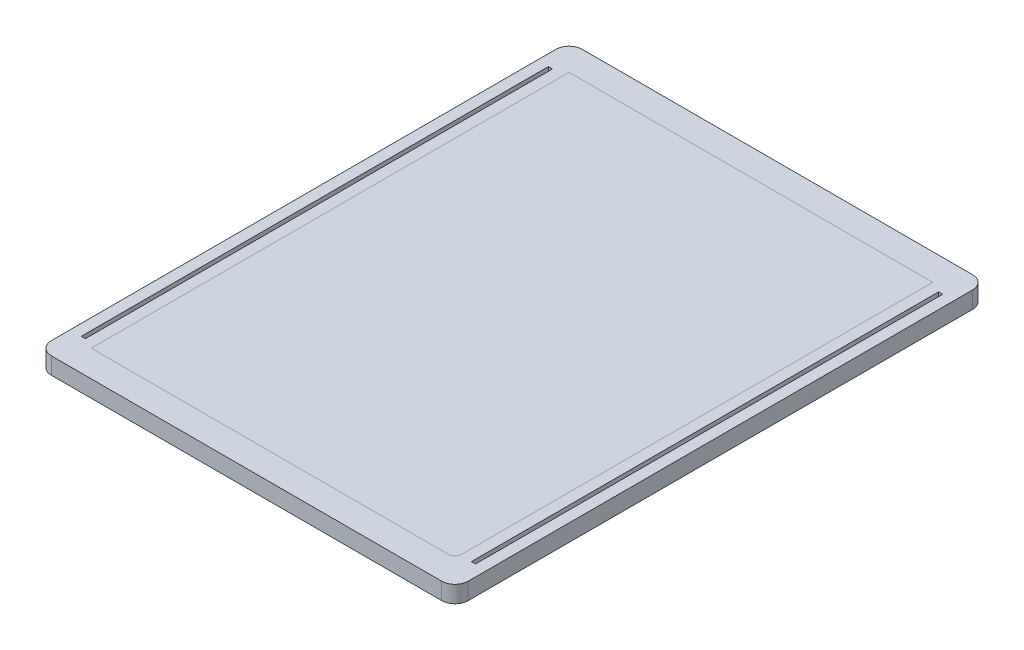
SolidWorks part; units mm, degrees
ref_plane "Front Plane" through (0, 0, 0) normal (0, 0, 1) x (1, 0, 0)
ref_plane "Top Plane" through (0, 0, 0) normal (0, 1, 0) x (1, 0, 0)
ref_plane "Right Plane" through (0, 0, 0) normal (1, 0, 0) x (0, 0, -1)
sketch "Sketch1" plane through (0, 0, 0) normal (0, 1, 0) x (1, 0, 0)
  line L0 (-68.5, 90) -> (68.5, 90)
  line L5 (-78.5, -100) -> (78.5, -100)
  line L6 (-78.5, -100) -> (-78.5, 100)
  line L7 (-78.5, 100) -> (78.5, 100)
  line L8 (78.5, -100) -> (78.5, 100)
  line L9 (-78.5, -100) -> (78.5, 100) construction
  line L10 (-78.5, 100) -> (78.5, -100) construction
  line L11 (68.5, -90) -> (68.5, 90)
  line L12 (-68.5, -90) -> (68.5, -90)
  line L13 (-68.5, -90) -> (-68.5, 90)
  line L32 (0, 100) -> (0, -100) construction
  point P0 (0, 0)
  dimension "D2" = 157
  dimension "D3" = 200
  dimension "D1" = 10
extrude "MainBody" add sketch "Sketch1" along normal mid plane 6.35
sketch "Sketch2" plane through (0, 3.175, 0) normal (0, 1, 0) x (1, 0, 0)
  line L0 (-68.5, 88) -> (-78.5, 88) construction
  line L4 (-68.5, 90) -> (-68.5, -90) construction
  line L10 (-78.5, 100) -> (-78.5, -100) construction
  line L11 (-73.5, 88) -> (-73.5, 0) construction
  line L12 (68.5, 90) -> (-68.5, 90) construction
  line L13 (78.5, 100) -> (-78.5, 100) construction
  line L18 (0, 0) -> (0, 100) construction
  line L27 (-74.2779, -88) -> (-72.7221, -88)
  line L28 (-74.2779, -88) -> (-74.2779, 88)
  line L29 (-74.2779, 88) -> (-72.7221, 88)
  line L30 (-72.7221, -88) -> (-72.7221, 88)
  line L31 (-74.2779, -88) -> (-72.7221, 88) construction
  line L32 (-74.2779, 88) -> (-72.7221, -88) construction
  dimension "D1" = 2
  dimension "D2" = 1.5557
extrude "SheetLock" cut sketch "Sketch2" against normal up to next
mirror "Mirror1" about plane through (0, 0, 0) normal (1, 0, 0) of "SheetLock"
sketch "Sketch3" plane through (0, 3.175, 0) normal (0, 1, 0) x (1, 0, 0)
  line L0 (0, 100) -> (0, -100) construction
  line L1 (78.5, 100) -> (-78.5, 100) construction
  line L2 (-78.5, -100) -> (78.5, -100) construction
  line L3 (-78.5, 0) -> (78.5, 0) construction
  line L4 (-78.5, 100) -> (-78.5, -100) construction
  line L5 (78.5, -100) -> (78.5, 100) construction
  line L6 (-68.5, 90) -> (-68.5, 100) construction
  line L7 (-68.5, 90) -> (-78.5, 90) construction
  circle A0 centre (-73.5, 95) radius 1.5
  circle A1 centre (73.5, 95) radius 1.5
  circle A2 centre (73.5, -95) radius 1.5
  circle A3 centre (-73.5, -95) radius 1.5
  point P19 (-68.5, 95)
  point P20 (-73.5, 90)
  dimension "D1" = 3
extrude "SupportHoles" [suppressed] cut sketch "Sketch3" against normal up to next
sketch "Sketch4" plane through (68.5, 0, 0) normal (-1, 0, 0) x (0, 0, 1)
  line L4 (-90, -3.175) -> (90, -3.175)
  line L5 (90, -3.175) -> (90, 3.175)
  line L6 (90, 3.175) -> (-90, 3.175)
  line L7 (-90, 3.175) -> (-90, -3.175)
  line L8 (-90, -3.175) -> (90, -3.175)
  line L9 (90, -3.175) -> (90, 3.175)
  line L10 (90, 3.175) -> (-90, 3.175)
  line L11 (-90, 3.175) -> (-90, -3.175)
  dimension "D1" = 0
extrude "Boss-Extrude1" add sketch "Sketch4" along normal up to surface (137 mm away) separate body up to face at (-68.5, 0, 0)
fillet "Fillet1" radius 5 4 edges at (-78.5, 0, -100) (-78.5, 0, 100) (78.5, 0, 100) (78.5, 0, -100)
fillet "Fillet2" radius 2.5 4 edges at (-68.5, 0, 90) (68.5, 0, 90) (68.5, 0, -90) (-68.5, 0, -90)
equation "\"SheetLockLengthOffset\"=2"
equation "\"SheetThickness\"=0.79375"
equation "\"SheetThicknessTolerance\"= 0.015in"
equation "\"LowerBasketWidth\"=157"
equation "\"D2@Sketch1\"=\"LowerBasketWidth\""
equation "\"LowerBasketLength\"=200"
equation "\"D3@Sketch1\"=\"LowerBasketLength\""
equation "\"SupportHoleDiameter\"=3"
equation "\"D1@Sketch3\"=\"SupportHoleDiameter\""
equation "\"InnerGapOffset\"=10"
equation "\"D1@Sketch1\"=\"InnerGapOffset\""
equation "\"D1@Sketch2\"=\"SheetLockLengthOffset\""
equation "\"D2@Sketch2\"=\"SheetThickness\" + \"SheetThicknessTolerance\"*2"
